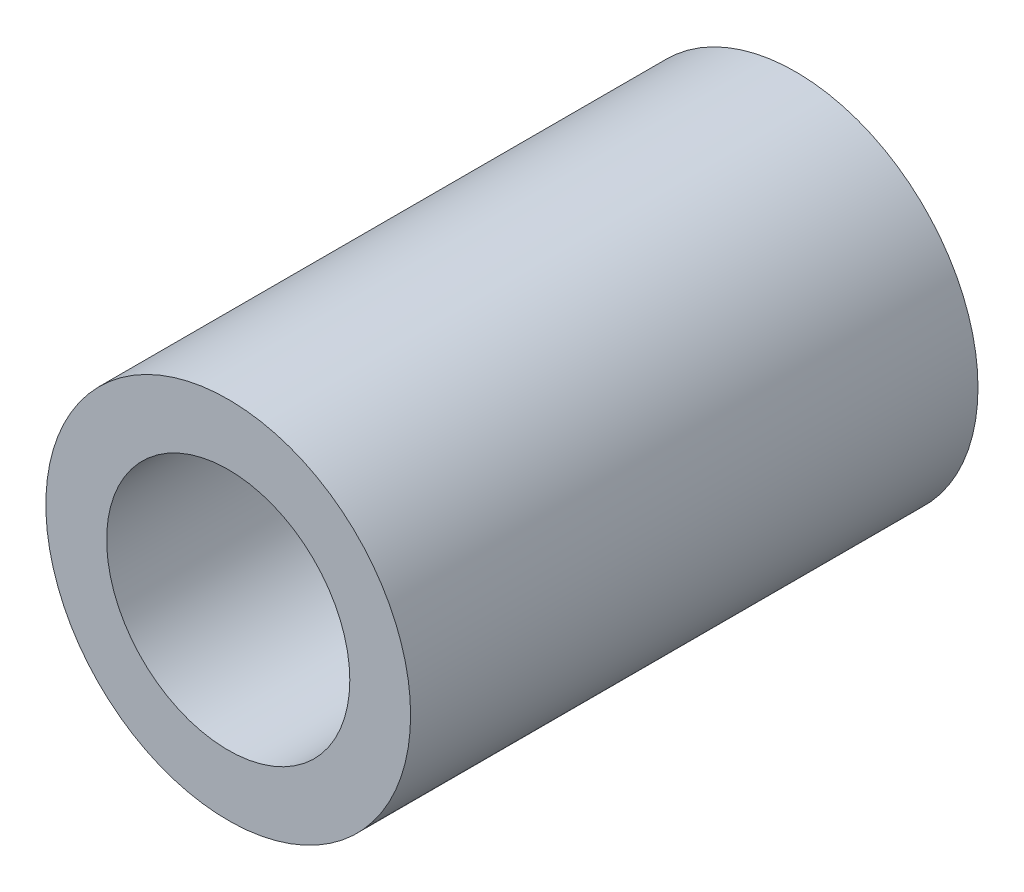
SolidWorks part; units mm, degrees
ref_plane "Спереди" through (0, 0, 0) normal (0, 0, 1) x (1, 0, 0)
ref_plane "Сверху" through (0, 0, 0) normal (0, 1, 0) x (1, 0, 0)
ref_plane "Справа" through (0, 0, 0) normal (1, 0, 0) x (0, 0, -1)
sketch "Эскиз1" plane through (0, 0, 0) normal (0, 0, 1) x (1, 0, 0)
  circle A0 centre (0, 0) radius 18
  circle A1 centre (0, 0) radius 12
  dimension "D1" = 36
  dimension "D2" = 24
extrude "Бобышка-Вытянуть1" add sketch "Эскиз1" against normal blind 56 contours A0 A1
